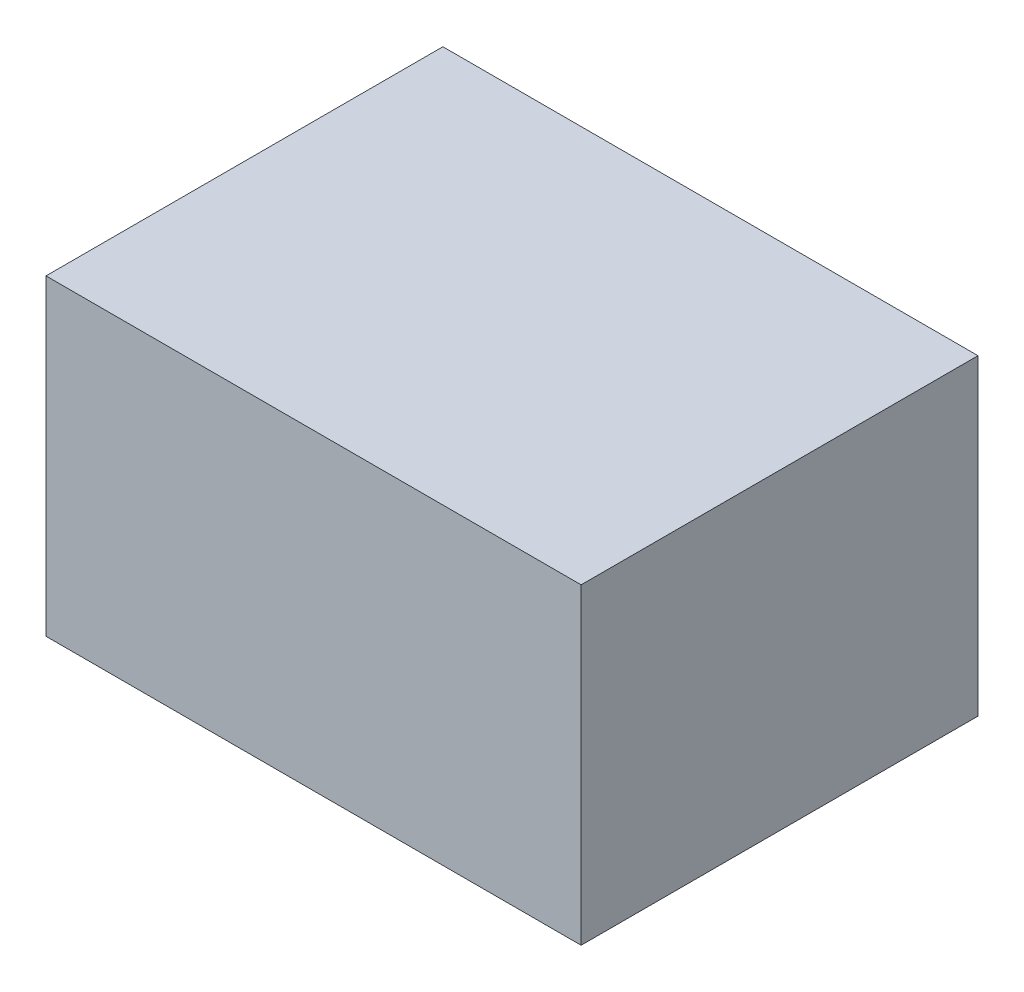
SolidWorks part; units mm, degrees
ref_plane "Front Plane" through (0, 0, 0) normal (0, 0, 1) x (1, 0, 0)
ref_plane "Top Plane" through (0, 0, 0) normal (0, 1, 0) x (1, 0, 0)
ref_plane "Right Plane" through (0, 0, 0) normal (1, 0, 0) x (0, 0, -1)
sketch "Sketch1" plane through (0, 0, 0) normal (0, 0, 1) x (1, 0, 0)
  line L1 (0, 0) -> (600, 0)
  line L2 (0, 0) -> (0, 350)
  line L3 (0, 350) -> (600, 350)
  line L4 (600, 0) -> (600, 350)
  dimension "D1" = 350
  dimension "D2" = 600
extrude "Boss-Extrude1" add sketch "Sketch1" against normal blind 445
